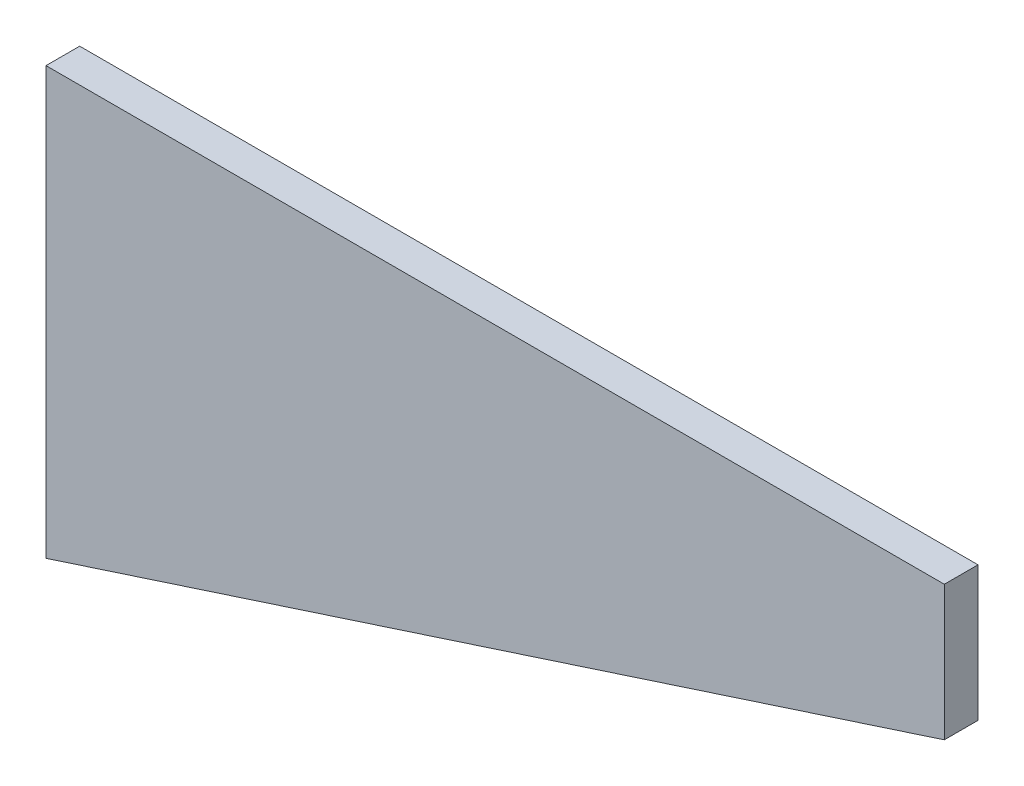
SolidWorks part; units mm, degrees
ref_plane "Plan de face" through (0, 0, 0) normal (0, 0, 1) x (1, 0, 0)
ref_plane "Plan de dessus" through (0, 0, 0) normal (0, 1, 0) x (1, 0, 0)
ref_plane "Plan de droite" through (0, 0, 0) normal (1, 0, 0) x (0, 0, -1)
sketch "Esquisse1" plane through (0, 0, 0) normal (0, 0, 1) x (1, 0, 0)
  line L0 (0, -469.4099) -> (400, -469.4099)
  line L2 (400, -469.4099) -> (400, -529.4099)
  line L3 (400, -529.4099) -> (0, -659.4099)
  line L4 (0, -659.4099) -> (0, -469.4099)
  dimension "D1" = 400
  dimension "D2" = 60
  dimension "D3" = 190
extrude "Boss.-Extru.1" add sketch "Esquisse1" against normal blind 15
